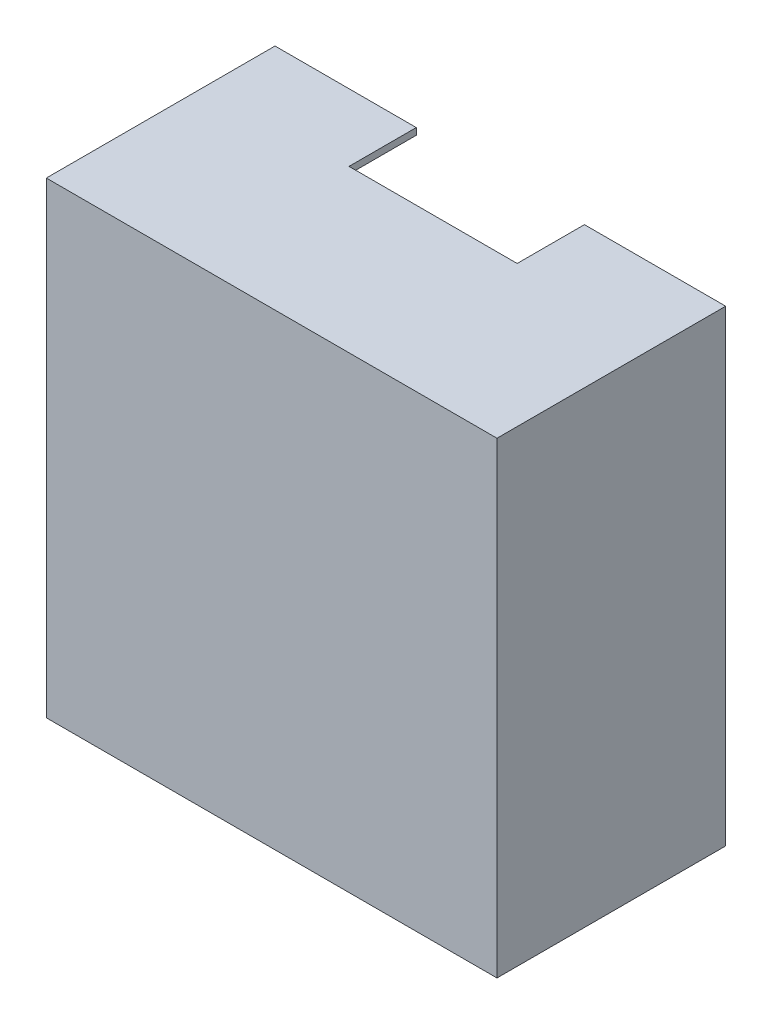
SolidWorks part; units mm, degrees
ref_plane "前视基准面" through (0, 0, 0) normal (0, 0, 1) x (1, 0, 0)
ref_plane "上视基准面" through (0, 0, 0) normal (0, 1, 0) x (1, 0, 0)
ref_plane "右视基准面" through (0, 0, 0) normal (1, 0, 0) x (0, 0, -1)
sketch "草图1" plane through (0, 0, 0) normal (0, 1, 0) x (1, 0, 0)
  line L1 (134, -68) -> (-134, -68)
  line L2 (134, -68) -> (134, 68)
  line L3 (134, 68) -> (-134, 68)
  line L4 (-134, -68) -> (-134, 68)
  line L5 (134, -68) -> (-134, 68) construction
  line L6 (134, 68) -> (-134, -68) construction
  point P0 (0, 0)
  dimension "D1" = 268
  dimension "D2" = 136
extrude "凸台-拉伸1" add sketch "草图1" along normal blind 278
sketch "草图2" plane through (0, 0, -68) normal (0, 0, -1) x (-1, 0, 0)
  line L14 (-130, 4) -> (130, 4)
  line L15 (130, 4) -> (130, 274)
  line L16 (130, 274) -> (-130, 274)
  line L17 (-130, 274) -> (-130, 4)
  line L18 (-130, 4) -> (130, 4)
  line L19 (130, 4) -> (130, 274)
  line L20 (130, 274) -> (-130, 274)
  line L21 (-130, 274) -> (-130, 4)
  dimension "D1" = 4
extrude "切除-拉伸1" cut sketch "草图2" against normal offset from surface (134 mm away) 2 up to face at (0, 139, 68)
sketch "草图3" plane through (0, 278, 0) normal (0, 1, 0) x (1, 0, 0)
  line L0 (0, 68) -> (0, -68) construction
  line L1 (134, 68) -> (-134, 68) construction
  line L2 (-134, -68) -> (134, -68) construction
  line L3 (50, 68) -> (-50, 68)
  line L4 (-50, 68) -> (-50, 28)
  line L5 (-50, 28) -> (50, 28)
  line L6 (50, 68) -> (50, 28)
  point P10 (0, 28)
  dimension "D1" = 40
  dimension "D2" = 100
extrude "切除-拉伸2" cut sketch "草图3" against normal up to next
sketch "草图4" plane through (0, 0, 0) normal (0, -1, 0) x (1, 0, 0)
  line L0 (0, 68) -> (0, -68) construction
  line L1 (-134, 68) -> (134, 68) construction
  line L2 (134, -68) -> (-134, -68) construction
  line L3 (-134, 0) -> (134, 0) construction
  line L4 (-134, -68) -> (-134, 68) construction
  line L5 (134, 68) -> (134, -68) construction
  line L6 (-134, 40) -> (-134, 44)
  line L7 (-134, 44) -> (-133, 44)
  line L8 (-133, 44) -> (-133, 40)
  line L9 (-133, 40) -> (-134, 40)
  line L10 (-133, -40) -> (-134, -40)
  line L11 (-133, -44) -> (-133, -40)
  line L12 (-134, -44) -> (-133, -44)
  line L13 (-134, -40) -> (-134, -44)
  line L14 (134, -40) -> (134, -44)
  line L15 (134, -44) -> (133, -44)
  line L16 (133, -44) -> (133, -40)
  line L17 (133, -40) -> (134, -40)
  line L18 (133, 40) -> (134, 40)
  line L19 (133, 44) -> (133, 40)
  line L20 (134, 44) -> (133, 44)
  line L21 (134, 40) -> (134, 44)
  dimension "D1" = 1
  dimension "D2" = 4
  dimension "D3" = 40
fillet "圆角1" [suppressed] radius 2
